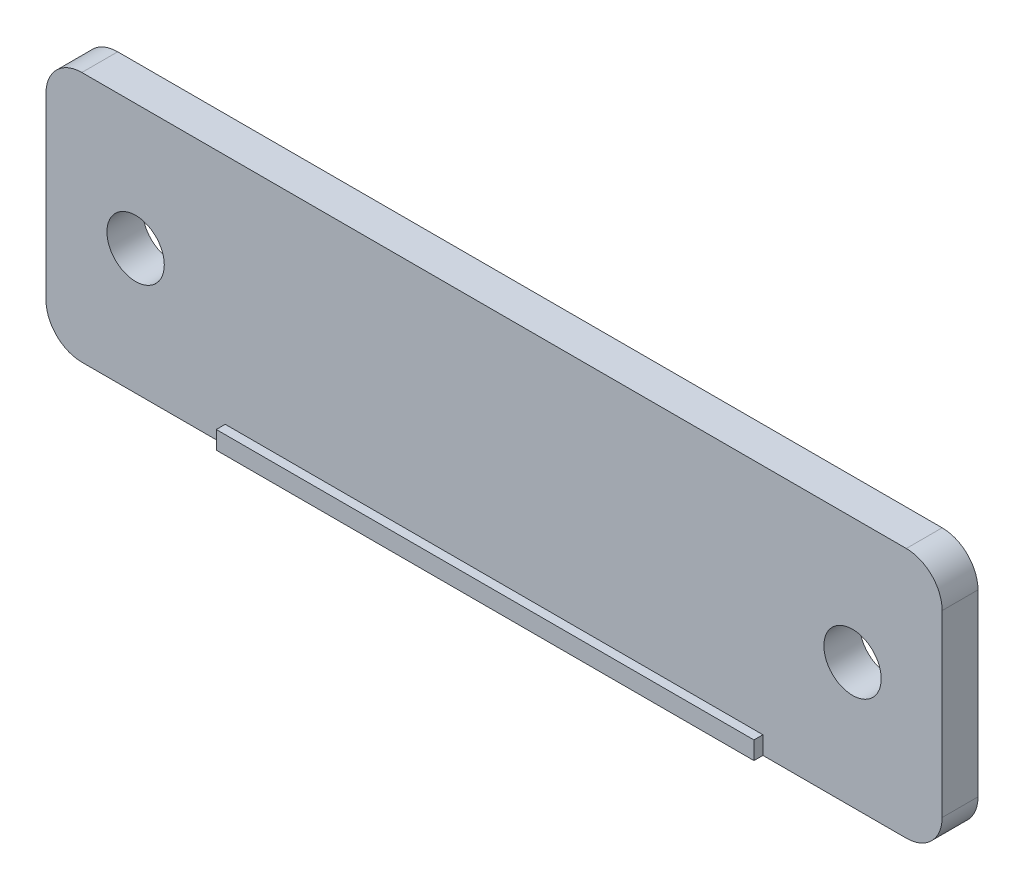
SolidWorks part; units mm, degrees
ref_plane "Front Plane" through (0, 0, 0) normal (0, 0, 1) x (1, 0, 0)
ref_plane "Top Plane" through (0, 0, 0) normal (0, 1, 0) x (1, 0, 0)
ref_plane "Right Plane" through (0, 0, 0) normal (1, 0, 0) x (0, 0, -1)
sketch "Sketch2" plane through (0, 0, 0) normal (0, 0, 1) x (1, 0, 0)
  line L1 (-25, -7) -> (25, -7)
  line L2 (-25, -7) -> (-25, 7)
  line L3 (-25, 7) -> (25, 7)
  line L4 (25, -7) -> (25, 7)
  line L5 (0, 7) -> (0, -7) construction
  line L6 (-25, 0) -> (25, 0) construction
  point P0 (0, 0)
  dimension "D1" = 50
  dimension "D2" = 14
extrude "Boss-Extrude1" add sketch "Sketch2" along normal blind 2.5
sketch "Sketch4" plane through (0, 0, 2.5) normal (0, 0, 1) x (1, 0, 0)
  line L0 (15, -6) -> (15, -7)
  line L1 (15, -6) -> (-15, -6)
  line L2 (15, -7) -> (-15, -7)
  line L3 (-15, -6) -> (-15, -7)
  line L4 (15, -6) -> (-15, -7) construction
  line L5 (15, -7) -> (-15, -6) construction
  point P0 (0, -7)
  point P1 (0, -6.5)
  point P2 (-15, -6.5)
  dimension "D1" = 0.5
  dimension "D2" = 15
extrude "Cut-Extrude1" cut sketch "Sketch4" against normal blind 0.5 flip side to cut
sketch "Sketch5" plane through (0, 0, 2) normal (0, 0, 1) x (1, 0, 0)
  line L0 (-20, 7) -> (-20, -7) construction
  line L1 (25, 7) -> (-25, 7) construction
  line L2 (-25, -7) -> (-15, -7) construction
  line L3 (-25, 7) -> (-25, -7) construction
  line L4 (20, 7) -> (20, -7) construction
  line L5 (15, -7) -> (25, -7) construction
  line L6 (25, -7) -> (25, 7) construction
  circle A0 centre (-20, 0) radius 1.6
  circle A1 centre (20, 0) radius 1.6
  dimension "D2" = 3.2
  dimension "D4" = 3.2
  dimension "D1" = 5
  dimension "D3" = 5
extrude "Cut-Extrude2" cut sketch "Sketch5" against normal blind 2
fillet "Fillet2" radius 2 4 edges at (-25, -7, 1) (25, -7, 1) (25, 7, 1) (-25, 7, 1)
sketch "Sketch6" plane through (0, 0, 2) normal (0, 0, 1) x (1, 0, 0)
  line L0 (-15, -6) -> (-15, 7) construction
  line L1 (23, 7) -> (-23, 7) construction
  line L2 (15, -6) -> (15, 7) construction
  line L3 (-9, 1) -> (-9, 5)
  line L4 (0, 7) -> (0, -6) construction
  line L5 (15, -6) -> (-15, -6) construction
  line L6 (7.5, 7) -> (7.5, -6) construction
  line L7 (-7.5, 7) -> (-7.5, -6) construction
  line L8 (15, -6) -> (-15, -6) construction
  line L9 (-15, -4.5) -> (15, -4.5) construction
  line L10 (-15, 5.5) -> (15, 5.5) construction
  line L11 (-13.75, 5.5) -> (-13.75, -4.5) construction
  line L12 (-8.75, 5.5) -> (-8.75, -4.5) construction
  line L13 (-6.25, 5.5) -> (-6.25, -4.5) construction
  line L14 (-1.25, 5.5) -> (-1.25, -4.5) construction
  line L15 (1.25, 5.5) -> (1.25, -4.5) construction
  line L16 (6.25, 5.5) -> (6.25, -4.5) construction
  line L17 (8.75, 5.5) -> (8.75, -4.5) construction
  line L18 (13.75, 5.5) -> (13.75, -4.5) construction
  line L19 (-15, 0.5) -> (15, 0.5) construction
  line L20 (-13.25, -4.25) -> (-9.25, -4.25)
  line L21 (-13.25, 5.75) -> (-9.25, 5.75)
  line L22 (-13.25, 5.75) -> (-13.25, 5.25) construction
  line L23 (-13.25, 5.25) -> (-9.25, 5.25)
  line L24 (-9.25, 5.75) -> (-9.25, 5.25) construction
  line L25 (-11.25, 5.25) -> (-11.25, 5.75) construction
  line L26 (-13.25, 5.5) -> (-9.25, 5.5) construction
  line L27 (-9.25, -4.75) -> (-9.25, -4.25) construction
  line L28 (-13.25, -4.75) -> (-9.25, -4.75)
  line L29 (-13.25, -4.75) -> (-13.25, -4.25) construction
  line L30 (-13.5, 0) -> (-13.5, -4)
  line L31 (-14, 1) -> (-13.5, 1) construction
  line L32 (-14, 1) -> (-14, 5)
  line L33 (-14, 5) -> (-13.5, 5) construction
  line L34 (-13.5, 1) -> (-13.5, 5)
  line L35 (-13.75, 5) -> (-13.75, 1) construction
  line L36 (-14, 3) -> (-13.5, 3) construction
  line L37 (-14, 0) -> (-14, -4)
  line L38 (-14, 0) -> (-13.5, 0) construction
  line L39 (-14, -4) -> (-13.5, -4) construction
  line L40 (-9, 1) -> (-8.5, 1) construction
  line L41 (-8.5, 1) -> (-8.5, 5)
  line L42 (-9, 5) -> (-8.5, 5) construction
  line L43 (-9, 0) -> (-8.5, 0) construction
  line L44 (-8.5, 0) -> (-8.5, -4)
  line L45 (-9, -4) -> (-8.5, -4) construction
  line L46 (-9, 0) -> (-9, -4)
  line L51 (-5.75, 0.75) -> (-5.75, 0.25) construction
  line L52 (-5.75, 0.75) -> (-1.75, 0.75)
  line L53 (-1.75, 0.75) -> (-1.75, 0.25) construction
  line L54 (-5.75, 0.25) -> (-1.75, 0.25)
  line L59 (-13.25, 0.75) -> (-13.25, 0.25)
  line L60 (-13.25, 0.25) -> (-9.25, 0.25)
  line L61 (-9.25, 0.75) -> (-9.25, 0.25)
  line L62 (-13.25, 0.75) -> (-9.25, 0.75)
  line L63 (-5.75, 5.75) -> (-5.75, 5.25)
  line L64 (-5.75, 5.25) -> (-1.75, 5.25)
  line L65 (-1.75, 5.75) -> (-1.75, 5.25)
  line L66 (-5.75, 5.75) -> (-1.75, 5.75)
  line L67 (-6, 1) -> (-6.5, 1) construction
  line L68 (-6.5, 1) -> (-6.5, 5)
  line L69 (-6, 5) -> (-6.5, 5) construction
  line L70 (-6, 1) -> (-6, 5)
  line L71 (-1, 0) -> (-1.5, 0) construction
  line L72 (-1, 0) -> (-1, -4)
  line L73 (-1, -4) -> (-1.5, -4) construction
  line L74 (-1.5, 0) -> (-1.5, -4)
  line L75 (-1, 5) -> (-1.5, 5) construction
  line L76 (-1.5, 1) -> (-1.5, 5)
  line L77 (-1, 1) -> (-1.5, 1) construction
  line L78 (-1, 1) -> (-1, 5)
  line L95 (14, 0) -> (13.5, 0) construction
  line L96 (14, 0) -> (14, -4)
  line L97 (14, -4) -> (13.5, -4) construction
  line L98 (13.5, 0) -> (13.5, -4)
  line L99 (13.25, 5.25) -> (9.25, 5.25)
  line L100 (9.25, 5.75) -> (9.25, 5.25) construction
  line L101 (13.25, 5.75) -> (9.25, 5.75)
  line L102 (13.25, 5.75) -> (13.25, 5.25) construction
  line L103 (14, 5) -> (13.5, 5) construction
  line L104 (13.5, 1) -> (13.5, 5)
  line L105 (14, 1) -> (13.5, 1) construction
  line L106 (14, 1) -> (14, 5)
  line L107 (1.5, 1) -> (1.5, 5)
  line L108 (1, 1) -> (1, 5)
  line L109 (1.75, 0.25) -> (5.75, 0.25)
  line L110 (1.75, 0.75) -> (5.75, 0.75)
  line L111 (6.5, 1) -> (6.5, 5)
  line L112 (6, 1) -> (6, 5)
  line L113 (6.5, 0) -> (6.5, -4)
  line L114 (6, 0) -> (6, -4)
  line L115 (9.25, 5.75) -> (9, 5.5)
  line L116 (9, 5.5) -> (9.25, 5.25)
  line L117 (13.25, 5.75) -> (13.5, 5.5)
  line L118 (13.5, 5.5) -> (13.25, 5.25)
  line L119 (13.5, 5) -> (13.75, 5.25)
  line L120 (13.75, 5.25) -> (14, 5)
  line L121 (13.5, 1) -> (13.75, 0.75)
  line L122 (13.75, 0.75) -> (14, 1)
  line L123 (13.5, 0) -> (13.75, 0.25)
  line L124 (13.75, 0.25) -> (14, 0)
  line L125 (14, -4) -> (13.75, -4.25)
  line L126 (13.75, -4.25) -> (13.5, -4)
  arc A0 (-14, 5) -> (-13.5, 5) centre (-13.75, 5) cw
  arc A1 (-13.25, 5.25) -> (-13.25, 5.75) centre (-13.25, 5.5) cw
  arc A2 (-9.25, 5.75) -> (-9.25, 5.25) centre (-9.25, 5.5) cw
  arc A3 (-9, 5) -> (-8.5, 5) centre (-8.75, 5) cw
  arc A4 (-8.5, 1) -> (-9, 1) centre (-8.75, 1) cw
  arc A5 (-9, 0) -> (-8.5, 0) centre (-8.75, 0) cw
  arc A6 (-14, 1) -> (-13.5, 1) centre (-13.75, 1) ccw
  arc A7 (-8.5, -4) -> (-9, -4) centre (-8.75, -4) cw
  arc A8 (-9.25, -4.25) -> (-9.25, -4.75) centre (-9.25, -4.5) cw
  arc A9 (-13.25, -4.75) -> (-13.25, -4.25) centre (-13.25, -4.5) cw
  arc A10 (-13.5, -4) -> (-14, -4) centre (-13.75, -4) cw
  arc A11 (-5.75, 0.25) -> (-5.75, 0.75) centre (-5.75, 0.5) cw
  arc A12 (-6.5, 1) -> (-6, 1) centre (-6.25, 1) ccw
  arc A13 (-1.75, 0.75) -> (-1.75, 0.25) centre (-1.75, 0.5) cw
  arc A14 (-1.5, 0) -> (-1, 0) centre (-1.25, 0) cw
  arc A15 (-1.5, 1) -> (-1, 1) centre (-1.25, 1) ccw
  arc A16 (-1.5, -4) -> (-1, -4) centre (-1.25, -4) ccw
  arc A17 (-6.5, 5) -> (-6, 5) centre (-6.25, 5) cw
  arc A18 (-1.5, 5) -> (-1, 5) centre (-1.25, 5) cw
  arc A19 (1, 5) -> (1.5, 5) centre (1.25, 5) cw
  arc A20 (1, 1) -> (1.5, 1) centre (1.25, 1) ccw
  arc A21 (1.75, 0.25) -> (1.75, 0.75) centre (1.75, 0.5) cw
  arc A22 (5.75, 0.75) -> (5.75, 0.25) centre (5.75, 0.5) cw
  arc A23 (6, 1) -> (6.5, 1) centre (6.25, 1) ccw
  arc A24 (6, 5) -> (6.5, 5) centre (6.25, 5) cw
  arc A25 (6, 0) -> (6.5, 0) centre (6.25, 0) cw
  arc A26 (6, -4) -> (6.5, -4) centre (6.25, -4) ccw
  arc A27 (-14, 0) -> (-13.5, 0) centre (-13.75, 0) cw
  point P40 (-11.25, 5.5)
  point P48 (-13.75, 3)
  dimension "D1" = 7.5
  dimension "D2" = 7.5
  dimension "D3" = 7.5
  dimension "D4" = 1.5
  dimension "D5" = 1.5
  dimension "D6" = 1.25
  dimension "D7" = 1.25
  dimension "D8" = 2.5
  dimension "D9" = 4
  dimension "D10" = 0.5
  dimension "D11" = 2.5
  dimension "D12" = 4
  dimension "D13" = 0.5
  dimension "D15" = 0.25
  dimension "D18" = 0.25
  dimension "D19" = 4
  dimension "D20" = 0.5
  dimension "D22" = 0.25
  dimension "D23" = 0.5
  dimension "D14" = 0.5
  dimension "D24" = 0.5
  dimension "D16" = 2
  dimension "D17" = 2
  dimension "D21" = 2
